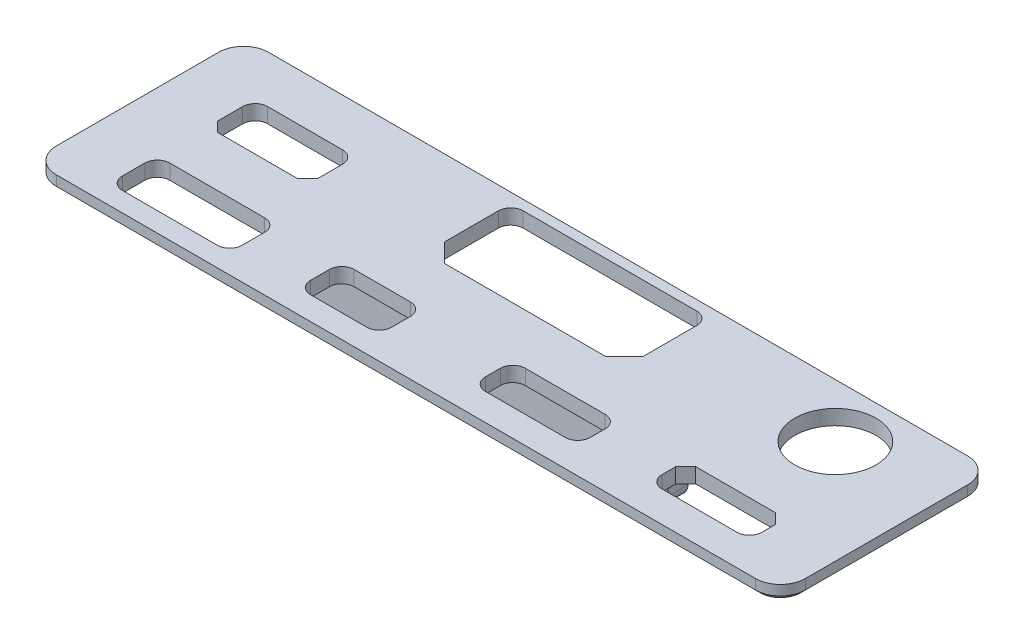
SolidWorks part; units mm, degrees
ref_plane "前视基准面" through (0, 0, 0) normal (0, 0, 1) x (1, 0, 0)
ref_plane "上视基准面" through (0, 0, 0) normal (0, 1, 0) x (1, 0, 0)
ref_plane "右视基准面" through (0, 0, 0) normal (1, 0, 0) x (0, 0, -1)
sketch "草图1" plane through (0, 0, 0) normal (0, 1, 0) x (1, 0, 0)
  line L1 (-30, 8.5) -> (30, 8.5)
  line L2 (-30, 8.5) -> (-30, -8.5)
  line L3 (-30, -8.5) -> (30, -8.5)
  line L4 (30, 8.5) -> (30, -8.5)
  line L5 (-30, 8.5) -> (30, -8.5) construction
  line L6 (-30, -8.5) -> (30, 8.5) construction
  point P0 (0, 0)
  dimension "D1" = 60
  dimension "D2" = 17
extrude "凸台-拉伸1" add sketch "草图1" along normal blind 1.2
sketch "草图4" plane through (0, 1.2, 0) normal (0, 1, 0) x (1, 0, 0)
  line L0 (-30, 8.5) -> (-30, -8.5) construction
  line L1 (-25.2717, 4.7) -> (-17.2717, 4.7)
  line L2 (-25.2717, 4.7) -> (-25.2717, 0.9)
  line L3 (-25.2717, 0.9) -> (-17.2717, 0.9)
  line L4 (-17.2717, 4.7) -> (-17.2717, 0.9)
  line L5 (-7.8, 7.7) -> (8.1, 7.7)
  line L6 (-7.8, 7.7) -> (-7.8, 0.9)
  line L7 (-7.8, 0.9) -> (8.1, 0.9)
  line L8 (8.1, 7.7) -> (8.1, 0.9)
  line L13 (17.05, -3.1348) -> (25.05, -3.1348)
  line L14 (17.05, -3.1348) -> (17.05, -6.0348)
  line L15 (17.05, -6.0348) -> (25.05, -6.0348)
  line L16 (25.05, -3.1348) -> (25.05, -6.0348)
  line L17 (3.2, -3.1348) -> (11.6, -3.1348)
  line L18 (3.2, -3.1348) -> (3.2, -6.3348)
  line L19 (3.2, -6.3348) -> (11.6, -6.3348)
  line L20 (11.6, -3.1348) -> (11.6, -6.3348)
  line L21 (-10.5, -3.1348) -> (-4, -3.1348)
  line L22 (-10.5, -3.1348) -> (-10.5, -6.6348)
  line L23 (-10.5, -6.6348) -> (-4, -6.6348)
  line L24 (-4, -3.1348) -> (-4, -6.6348)
  line L25 (-25.2717, -3.1348) -> (-15.6717, -3.1348)
  line L26 (-25.2717, -3.1348) -> (-25.2717, -6.9348)
  line L27 (-25.2717, -6.9348) -> (-15.6717, -6.9348)
  line L28 (-15.6717, -3.1348) -> (-15.6717, -6.9348)
  line L29 (30, 8.5) -> (-30, 8.5) construction
  line L31 (30, -8.5) -> (30, 8.5) construction
  line L32 (30, 8.5) -> (-30, 8.5) construction
  circle A0 centre (21.7, 4.2) radius 3.25
  point P8 (0, 0)
  point P30 (0, 0)
  point P35 (0, 0)
  dimension "D21" = 6.5
  dimension "D1" = 3.5
  dimension "D2" = 6.5
  dimension "D3" = 8.4
  dimension "D4" = 3.2
  dimension "D5" = 8
  dimension "D6" = 3.8
  dimension "D7" = 15.9
  dimension "D8" = 8
  dimension "D9" = 2.9
  dimension "D10" = 4.7283
  dimension "D11" = 7.6
  dimension "D12" = 11.6348
  dimension "D13" = 19.5
  dimension "D14" = 33.2
  dimension "D15" = 4.95
  dimension "D17" = 22.2
  dimension "D19" = 8.3
  dimension "D20" = 4.3
  dimension "D22" = 6.8
  dimension "D23" = 9.6
extrude "切除-拉伸1" cut sketch "草图4" against normal up to next
fillet "圆角2" radius 1 18 edges at (-25.2717, 0.6, -4.7) (-17.2717, 0.6, -4.7) (8.1, 0.6, -7.7) (-7.8, 0.6, -7.7) (25.05, 0.6, 6.0348) (17.05, 0.6, 6.0348) (11.6, 0.6, 6.3348) (11.6, 0.6, 3.1348) (3.2, 0.6, 3.1348) (3.2, 0.6, 6.3348) (-4, 0.6, 6.6348) (-4, 0.6, 3.1348) (-10.5, 0.6, 3.1348) (-10.5, 0.6, 6.6348) (-15.6717, 0.6, 6.9348) (-15.6717, 0.6, 3.1348) (-25.2717, 0.6, 3.1348) (-25.2717, 0.6, 6.9348)
chamfer "倒角1" distance 0.8 angle 45 4 edges at (17.05, 0.6, 3.1348) (25.05, 0.6, 3.1348) (-17.2717, 0.6, -0.9) (-25.2717, 0.6, -0.9)
sketch "草图5" plane through (0, 0, 0) normal (0, -1, 0) x (1, 0, 0)
  line L0 (-30, -8.5) -> (-30, 8.5) construction
  line L1 (-13.9089, -3.3832) -> (-12.4089, -3.3832)
  line L2 (-13.9089, -3.3832) -> (-13.9089, 4.6168)
  line L3 (-13.9089, 4.6168) -> (-12.4089, 4.6168)
  line L4 (-12.4089, -3.3832) -> (-12.4089, 4.6168)
  line L5 (13.0911, -3.3832) -> (14.5911, -3.3832)
  line L6 (13.0911, -3.3832) -> (13.0911, 4.6168)
  line L7 (13.0911, 4.6168) -> (14.5911, 4.6168)
  line L8 (14.5911, -3.3832) -> (14.5911, 4.6168)
  line L9 (30, -8.5) -> (-30, -8.5) construction
  line L10 (30, 8.5) -> (30, -8.5) construction
  dimension "D1" = 1.5
  dimension "D2" = 8
  dimension "D3" = 1.5
  dimension "D4" = 8
  dimension "D5" = 16.0911
  dimension "D6" = 5.1168
  dimension "D7" = 5.1168
  dimension "D8" = 15.4089
extrude "凸台-拉伸2" add sketch "草图5" along normal blind 1.2
sketch "草图6" plane through (0, 0, 0) normal (0, -1, 0) x (1, 0, 0)
  line L0 (-13.9089, 4.6168) -> (-13.9089, -3.3832) construction
  line L1 (-13.9089, 2.1) -> (14.5911, 2.1)
  line L2 (-13.9089, 2.1) -> (-13.9089, 0.5)
  line L3 (-13.9089, 0.5) -> (14.5911, 0.5)
  line L4 (14.5911, 2.1) -> (14.5911, 0.5)
  line L5 (30, -8.5) -> (-30, -8.5) construction
  dimension "D1" = 1.6
  dimension "D2" = 9
extrude "凸台-拉伸3" add sketch "草图6" along normal blind 4
fillet "圆角3" radius 1 2 edges at (14.5911, -4, 1.3) (-13.9089, -4, 1.3)
chamfer "倒角2" distance 1 angle 45 4 edges at (13.8411, -1.2, -3.3832) (-13.1589, -1.2, -3.3832) (13.8411, -1.2, 4.6168) (-13.1589, -1.2, 4.6168)
fillet "圆角4" radius 2 4 edges at (30, 0.6, 8.5) (30, 0.6, -8.5) (-30, 0.6, 8.5) (-30, 0.6, -8.5)
chamfer "倒角5" distance 0.4 angle 45 8 edges at (0, 0, -8.5) (-29.4142, 0, -7.9142) (29.4142, 0, -7.9142) (-30, 0, 0) (30, 0, 0) (-29.4142, 0, 7.9142) (29.4142, 0, 7.9142) (0, 0, 8.5)
chamfer "倒角6" distance 1.5 angle 45 2 edges at (8.1, 0.6, -0.9) (-7.8, 0.6, -0.9)
